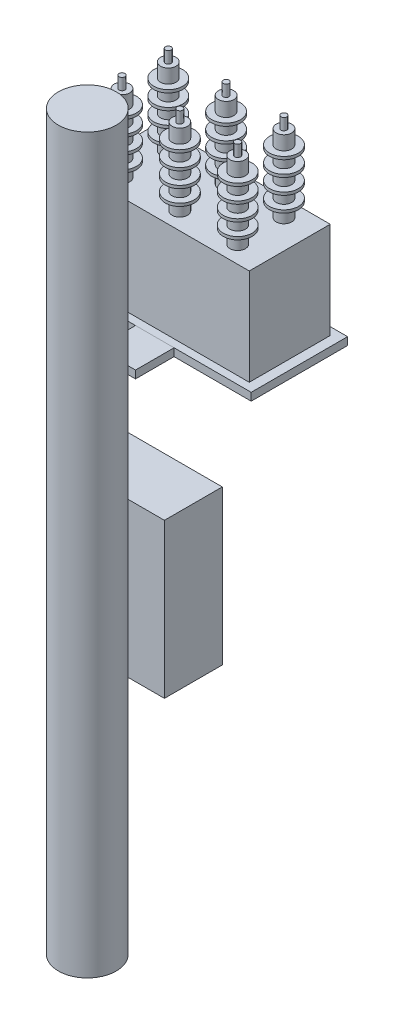
SolidWorks part; units mm, degrees
ref_plane "Front Plane" through (0, 0, 0) normal (0, 0, 1) x (1, 0, 0)
ref_plane "Top Plane" through (0, 0, 0) normal (0, 1, 0) x (1, 0, 0)
ref_plane "Right Plane" through (0, 0, 0) normal (1, 0, 0) x (0, 0, -1)
sketch "Sketch1" plane through (0, 0, 0) normal (0, 1, 0) x (1, 0, 0)
  line L1 (-450, -210) -> (450, -210)
  line L2 (-450, -210) -> (-450, 210)
  line L3 (-450, 210) -> (450, 210)
  line L4 (450, -210) -> (450, 210)
  line L5 (-450, -210) -> (450, 210) construction
  line L6 (-450, 210) -> (450, -210) construction
  point P0 (0, 0)
extrude "Tank" add sketch "Sketch1" along normal blind 500 separate body
sketch "Sketch2" plane through (0, 0, 0) normal (0, 1, 0) x (1, 0, 0)
  line L1 (-500, -250) -> (500, -250)
  line L2 (-500, -250) -> (-500, 250)
  line L3 (-500, 250) -> (500, 250)
  line L4 (500, -250) -> (500, 250)
  line L5 (-500, -250) -> (500, 250) construction
  line L6 (-500, 250) -> (500, -250) construction
  point P0 (0, 0)
extrude "Frame" add sketch "Sketch2" along normal blind 40 from offset 40 separate body
sketch "Sketch3" plane through (0, 0, 0) normal (0, 1, 0) x (1, 0, 0)
  line L0 (-500, -250) -> (500, -250) construction
  line L1 (-100, -450) -> (100, -450)
  line L2 (-100, -450) -> (-100, -250)
  line L3 (-100, -250) -> (100, -250)
  line L4 (100, -450) -> (100, -250)
  line L5 (-100, -450) -> (100, -250) construction
  line L6 (-100, -250) -> (100, -450) construction
  point P0 (0, -350)
extrude "Frame arm" add sketch "Sketch3" along normal blind 40 from offset 40 separate body
sketch "Sketch4" plane through (0, 0, 0) normal (0, 1, 0) x (1, 0, 0)
  line L1 (-250, -450) -> (250, -450)
  line L2 (-250, -450) -> (-250, -150)
  line L3 (-250, -150) -> (250, -150)
  line L4 (250, -450) -> (250, -150)
  line L5 (-250, -450) -> (250, -150) construction
  line L6 (-250, -150) -> (250, -450) construction
  point P0 (0, -300)
extrude "Control cabinet" add sketch "Sketch4" along normal blind 800 from offset 1400 separate body
sketch "Sketch5" plane through (0, 0, 0) normal (0, 1, 0) x (1, 0, 0)
  circle A0 centre (0, -600) radius 150
extrude "Pole" add sketch "Sketch5" along normal blind 3800 from offset 2600 separate body
sketch "Sketch6" plane through (0, 0, 0) normal (0, 1, 0) x (1, 0, 0)
  circle A0 centre (-300, 120) radius 40
extrude "Bushing Source A" add sketch "Sketch6" along normal blind 400 from offset 500 separate body
sketch "Sketch7" plane through (0, 0, 0) normal (0, 1, 0) x (1, 0, 0)
  circle A0 centre (-300, 120) radius 75
extrude "Shed Source A 1" add sketch "Sketch7" along normal blind 15 from offset 572.5 separate body
sketch "Sketch8" plane through (0, 0, 0) normal (0, 1, 0) x (1, 0, 0)
  circle A0 centre (-300, 120) radius 75
extrude "Shed Source A 2" add sketch "Sketch8" along normal blind 15 from offset 652.5 separate body
sketch "Sketch9" plane through (0, 0, 0) normal (0, 1, 0) x (1, 0, 0)
  circle A0 centre (-300, 120) radius 75
extrude "Shed Source A 3" add sketch "Sketch9" along normal blind 15 from offset 732.5 separate body
sketch "Sketch10" plane through (0, 0, 0) normal (0, 1, 0) x (1, 0, 0)
  circle A0 centre (-300, 120) radius 75
extrude "Shed Source A 4" add sketch "Sketch10" along normal blind 15 from offset 812.5 separate body
sketch "Sketch11" plane through (0, 0, 0) normal (0, 1, 0) x (1, 0, 0)
  circle A0 centre (-300, 120) radius 15
extrude "Terminal Source A" add sketch "Sketch11" along normal blind 60 from offset 900 separate body
sketch "Sketch12" plane through (0, 0, 0) normal (0, 1, 0) x (1, 0, 0)
  circle A0 centre (0, 120) radius 40
extrude "Bushing Source B" add sketch "Sketch12" along normal blind 400 from offset 500 separate body
sketch "Sketch13" plane through (0, 0, 0) normal (0, 1, 0) x (1, 0, 0)
  circle A0 centre (0, 120) radius 75
extrude "Shed Source B 1" add sketch "Sketch13" along normal blind 15 from offset 572.5 separate body
sketch "Sketch14" plane through (0, 0, 0) normal (0, 1, 0) x (1, 0, 0)
  circle A0 centre (0, 120) radius 75
extrude "Shed Source B 2" add sketch "Sketch14" along normal blind 15 from offset 652.5 separate body
sketch "Sketch15" plane through (0, 0, 0) normal (0, 1, 0) x (1, 0, 0)
  circle A0 centre (0, 120) radius 75
extrude "Shed Source B 3" add sketch "Sketch15" along normal blind 15 from offset 732.5 separate body
sketch "Sketch16" plane through (0, 0, 0) normal (0, 1, 0) x (1, 0, 0)
  circle A0 centre (0, 120) radius 75
extrude "Shed Source B 4" add sketch "Sketch16" along normal blind 15 from offset 812.5 separate body
sketch "Sketch17" plane through (0, 0, 0) normal (0, 1, 0) x (1, 0, 0)
  circle A0 centre (0, 120) radius 15
extrude "Terminal Source B" add sketch "Sketch17" along normal blind 60 from offset 900 separate body
sketch "Sketch18" plane through (0, 0, 0) normal (0, 1, 0) x (1, 0, 0)
  circle A0 centre (300, 120) radius 40
extrude "Bushing Source C" add sketch "Sketch18" along normal blind 400 from offset 500 separate body
sketch "Sketch19" plane through (0, 0, 0) normal (0, 1, 0) x (1, 0, 0)
  circle A0 centre (300, 120) radius 75
extrude "Shed Source C 1" add sketch "Sketch19" along normal blind 15 from offset 572.5 separate body
sketch "Sketch20" plane through (0, 0, 0) normal (0, 1, 0) x (1, 0, 0)
  circle A0 centre (300, 120) radius 75
extrude "Shed Source C 2" add sketch "Sketch20" along normal blind 15 from offset 652.5 separate body
sketch "Sketch21" plane through (0, 0, 0) normal (0, 1, 0) x (1, 0, 0)
  circle A0 centre (300, 120) radius 75
extrude "Shed Source C 3" add sketch "Sketch21" along normal blind 15 from offset 732.5 separate body
sketch "Sketch22" plane through (0, 0, 0) normal (0, 1, 0) x (1, 0, 0)
  circle A0 centre (300, 120) radius 75
extrude "Shed Source C 4" add sketch "Sketch22" along normal blind 15 from offset 812.5 separate body
sketch "Sketch23" plane through (0, 0, 0) normal (0, 1, 0) x (1, 0, 0)
  circle A0 centre (300, 120) radius 15
extrude "Terminal Source C" add sketch "Sketch23" along normal blind 60 from offset 900 separate body
sketch "Sketch24" plane through (0, 0, 0) normal (0, 1, 0) x (1, 0, 0)
  circle A0 centre (-300, -120) radius 40
extrude "Bushing Load A" add sketch "Sketch24" along normal blind 400 from offset 500 separate body
sketch "Sketch25" plane through (0, 0, 0) normal (0, 1, 0) x (1, 0, 0)
  circle A0 centre (-300, -120) radius 75
extrude "Shed Load A 1" add sketch "Sketch25" along normal blind 15 from offset 572.5 separate body
sketch "Sketch26" plane through (0, 0, 0) normal (0, 1, 0) x (1, 0, 0)
  circle A0 centre (-300, -120) radius 75
extrude "Shed Load A 2" add sketch "Sketch26" along normal blind 15 from offset 652.5 separate body
sketch "Sketch27" plane through (0, 0, 0) normal (0, 1, 0) x (1, 0, 0)
  circle A0 centre (-300, -120) radius 75
extrude "Shed Load A 3" add sketch "Sketch27" along normal blind 15 from offset 732.5 separate body
sketch "Sketch28" plane through (0, 0, 0) normal (0, 1, 0) x (1, 0, 0)
  circle A0 centre (-300, -120) radius 75
extrude "Shed Load A 4" add sketch "Sketch28" along normal blind 15 from offset 812.5 separate body
sketch "Sketch29" plane through (0, 0, 0) normal (0, 1, 0) x (1, 0, 0)
  circle A0 centre (-300, -120) radius 15
extrude "Terminal Load A" add sketch "Sketch29" along normal blind 60 from offset 900 separate body
sketch "Sketch30" plane through (0, 0, 0) normal (0, 1, 0) x (1, 0, 0)
  circle A0 centre (0, -120) radius 40
extrude "Bushing Load B" add sketch "Sketch30" along normal blind 400 from offset 500 separate body
sketch "Sketch31" plane through (0, 0, 0) normal (0, 1, 0) x (1, 0, 0)
  circle A0 centre (0, -120) radius 75
extrude "Shed Load B 1" add sketch "Sketch31" along normal blind 15 from offset 572.5 separate body
sketch "Sketch32" plane through (0, 0, 0) normal (0, 1, 0) x (1, 0, 0)
  circle A0 centre (0, -120) radius 75
extrude "Shed Load B 2" add sketch "Sketch32" along normal blind 15 from offset 652.5 separate body
sketch "Sketch33" plane through (0, 0, 0) normal (0, 1, 0) x (1, 0, 0)
  circle A0 centre (0, -120) radius 75
extrude "Shed Load B 3" add sketch "Sketch33" along normal blind 15 from offset 732.5 separate body
sketch "Sketch34" plane through (0, 0, 0) normal (0, 1, 0) x (1, 0, 0)
  circle A0 centre (0, -120) radius 75
extrude "Shed Load B 4" add sketch "Sketch34" along normal blind 15 from offset 812.5 separate body
sketch "Sketch35" plane through (0, 0, 0) normal (0, 1, 0) x (1, 0, 0)
  circle A0 centre (0, -120) radius 15
extrude "Terminal Load B" add sketch "Sketch35" along normal blind 60 from offset 900 separate body
sketch "Sketch36" plane through (0, 0, 0) normal (0, 1, 0) x (1, 0, 0)
  circle A0 centre (300, -120) radius 40
extrude "Bushing Load C" add sketch "Sketch36" along normal blind 400 from offset 500 separate body
sketch "Sketch37" plane through (0, 0, 0) normal (0, 1, 0) x (1, 0, 0)
  circle A0 centre (300, -120) radius 75
extrude "Shed Load C 1" add sketch "Sketch37" along normal blind 15 from offset 572.5 separate body
sketch "Sketch38" plane through (0, 0, 0) normal (0, 1, 0) x (1, 0, 0)
  circle A0 centre (300, -120) radius 75
extrude "Shed Load C 2" add sketch "Sketch38" along normal blind 15 from offset 652.5 separate body
sketch "Sketch39" plane through (0, 0, 0) normal (0, 1, 0) x (1, 0, 0)
  circle A0 centre (300, -120) radius 75
extrude "Shed Load C 3" add sketch "Sketch39" along normal blind 15 from offset 732.5 separate body
sketch "Sketch40" plane through (0, 0, 0) normal (0, 1, 0) x (1, 0, 0)
  circle A0 centre (300, -120) radius 75
extrude "Shed Load C 4" add sketch "Sketch40" along normal blind 15 from offset 812.5 separate body
sketch "Sketch41" plane through (0, 0, 0) normal (0, 1, 0) x (1, 0, 0)
  circle A0 centre (300, -120) radius 15
extrude "Terminal Load C" add sketch "Sketch41" along normal blind 60 from offset 900 separate body
